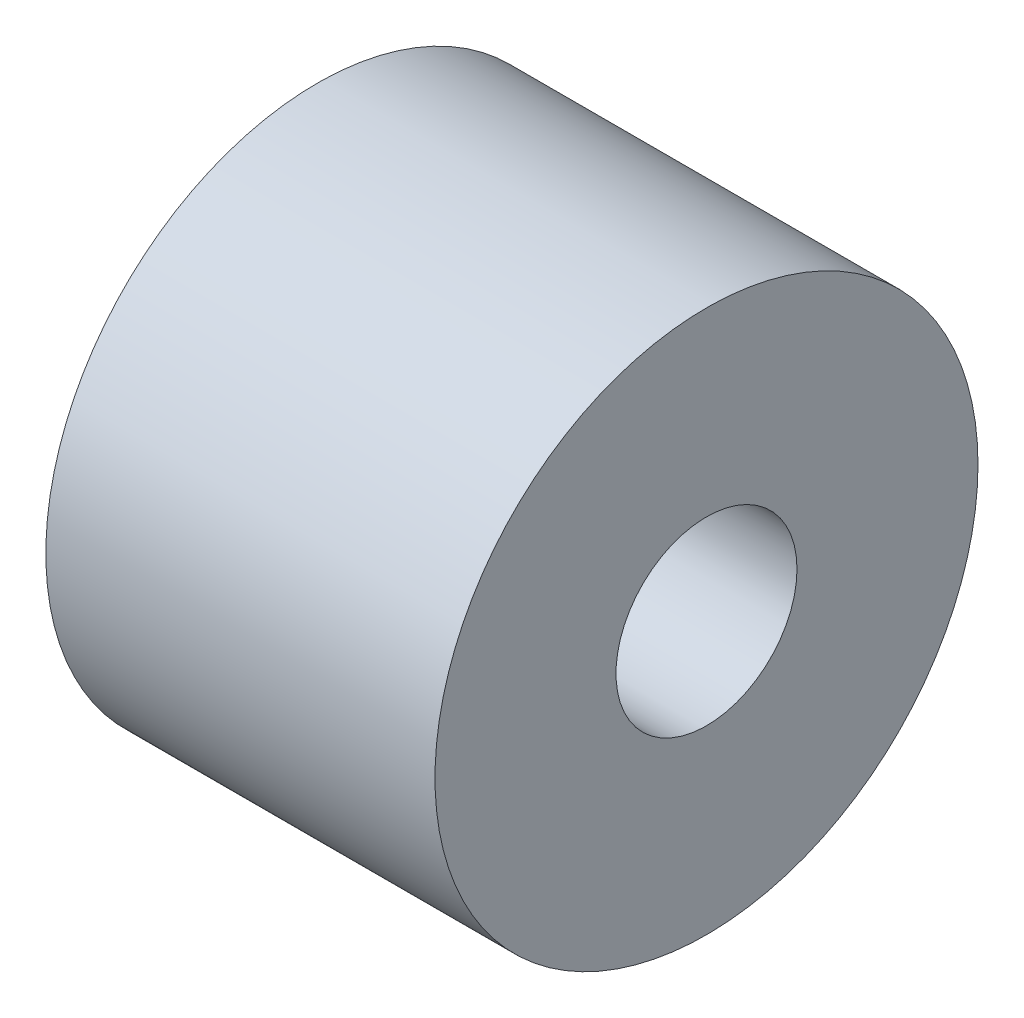
SolidWorks part; units mm, degrees
ref_plane "Спереди" through (0, 0, 0) normal (0, 0, 1) x (1, 0, 0)
ref_plane "Сверху" through (0, 0, 0) normal (0, 1, 0) x (1, 0, 0)
ref_plane "Справа" through (0, 0, 0) normal (1, 0, 0) x (0, 0, -1)
sketch "Эскиз1" plane through (0, 0, 0) normal (1, 0, 0) x (0, 0, -1)
  circle A0 centre (0, 0) radius 5
  circle A1 centre (0, 0) radius 15
extrude "Вытянуть1" add sketch "Эскиз1" along normal blind 21.5
